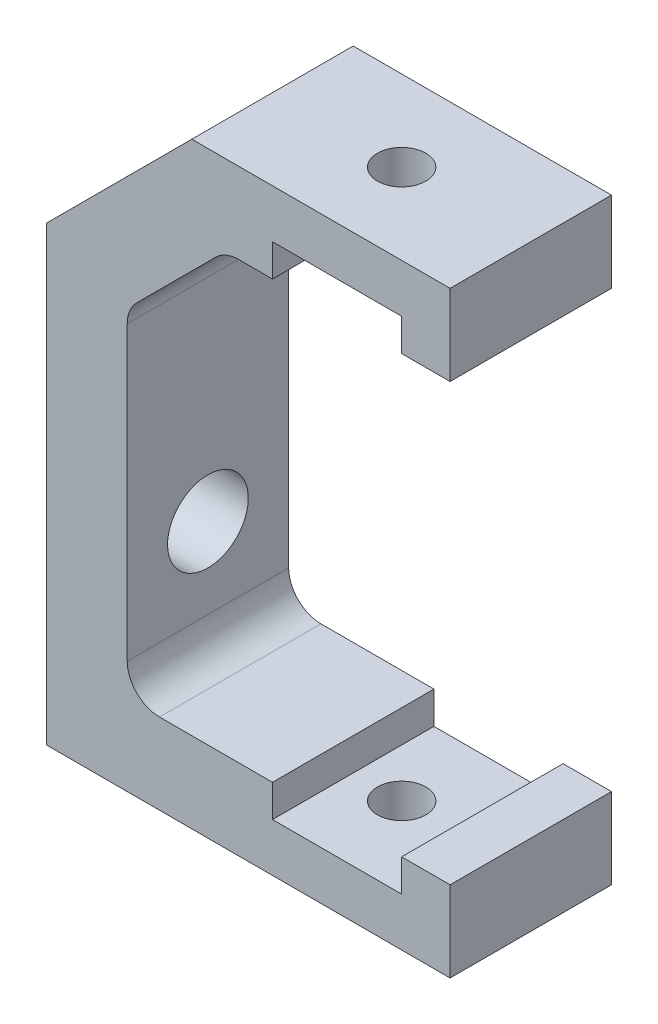
SolidWorks part; units mm, degrees
ref_plane "Front Plane" through (0, 0, 0) normal (0, 0, 1) x (1, 0, 0)
ref_plane "Top Plane" through (0, 0, 0) normal (0, 1, 0) x (1, 0, 0)
ref_plane "Right Plane" through (0, 0, 0) normal (1, 0, 0) x (0, 0, -1)
sketch "Sketch1" plane through (0, 0, 0) normal (0, 0, 1) x (1, 0, 0)
  line L0 (0, 0) -> (0, 28)
  line L1 (0, 28) -> (9, 37)
  line L2 (9, 37) -> (25, 37)
  line L3 (25, 37) -> (25, 32)
  line L4 (25, 32) -> (22, 32)
  line L5 (22, 32) -> (22, 34)
  line L6 (22, 34) -> (14, 34)
  line L7 (14, 34) -> (14, 32)
  line L8 (14, 32) -> (11.8995, 32)
  line L9 (10.4853, 31.4142) -> (5.5858, 26.5147)
  line L10 (5, 25.1005) -> (5, 7)
  line L11 (7, 5) -> (14, 5)
  line L12 (14, 5) -> (14, 3)
  line L13 (14, 3) -> (22, 3)
  line L14 (22, 3) -> (22, 5)
  line L15 (22, 5) -> (25, 5)
  line L16 (25, 5) -> (25, 0)
  line L17 (25, 0) -> (0, 0)
  line L18 (0, 28) -> (0, 41.7779) construction
  arc A0 (7, 5) -> (5, 7) centre (7, 7) cw
  arc A1 (10.4853, 31.4142) -> (11.8995, 32) centre (11.8995, 30) cw
  arc A2 (5, 25.1005) -> (5.5858, 26.5147) centre (7, 25.1005) cw
  point P26 (18, 34)
  point P27 (22, 4)
  point P28 (0, 0)
  point P29 (18, 3)
  point P30 (0, 0)
  point P31 (0, 0)
  point P32 (0, 0)
  point P33 (23.5, 32)
  point P34 (25, 35.4995)
  point P35 (0, 0)
  dimension "D3" = 2
  dimension "D1" = 28
  dimension "D2" = 45
  dimension "D4" = 2
  dimension "D5" = 5
  dimension "D6" = 8
  dimension "D7" = 3
  dimension "D8" = 25
  dimension "D9" = 2
  dimension "D10" = 5
  dimension "D11" = 5
  dimension "D12" = 5
  dimension "D13" = 37
extrude "Boss-Extrude1" add sketch "Sketch1" along normal mid plane 10
sketch "Sketch2" plane through (0, 37, 0) normal (0, 1, 0) x (1, 0, 0)
  line L0 (25, 5) -> (9, 5) construction
  line L1 (9, -5) -> (9, 5) construction
  circle A0 centre (17, 0) radius 1.5
  point P4 (17, 5)
  point P5 (9, 0)
  point P6 (0, 0)
  point P9 (0, 0)
  point P10 (0, 0)
  point P11 (0, 0)
  dimension "D1" = 3
extrude "Cut-Extrude1" cut sketch "Sketch2" against normal up to surface (37 mm away) up to face at (12.5, 0, 0)
sketch "Sketch3" plane through (5, 0, 0) normal (1, 0, 0) x (0, 0, -1)
  circle A0 centre (0, 12) radius 2.5
  point P2 (0, 0)
  dimension "D1" = 5
  dimension "D2" = 12
extrude "Cut-Extrude2" cut sketch "Sketch3" against normal up to surface (5 mm away) up to face at (0, 14, 0)
